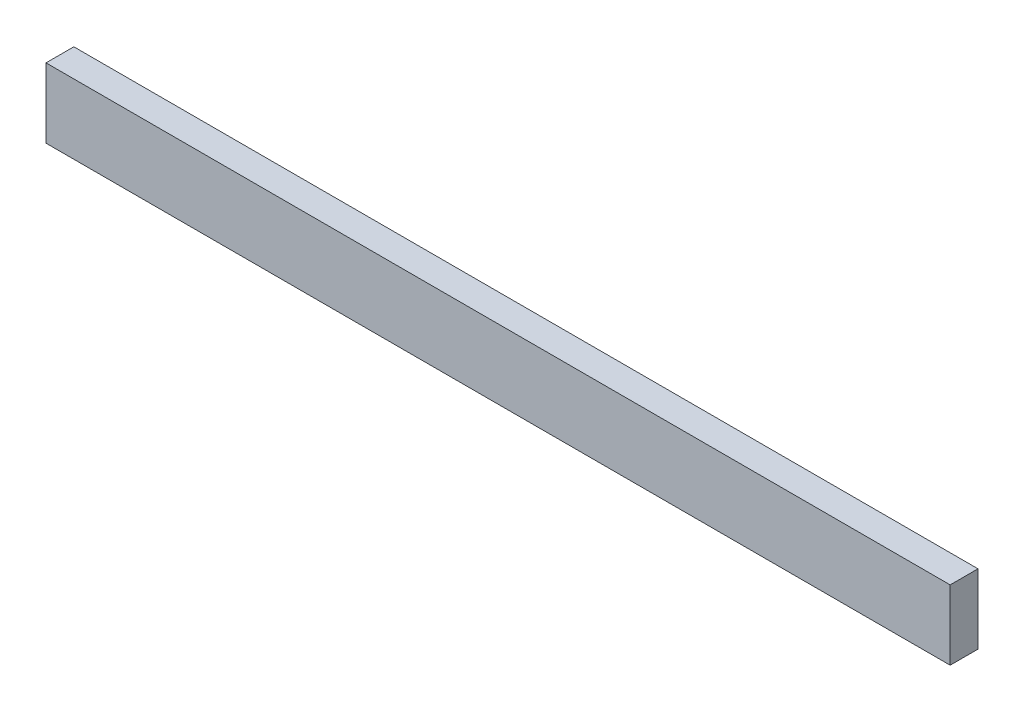
SolidWorks part; units mm, degrees
material "Cedar"
ref_plane "Front Plane" through (0, 0, 0) normal (0, 0, 1) x (1, 0, 0)
ref_plane "Top Plane" through (0, 0, 0) normal (0, 1, 0) x (1, 0, 0)
ref_plane "Right Plane" through (0, 0, 0) normal (1, 0, 0) x (0, 0, -1)
sketch "Sketch1" plane through (0, 0, 0) normal (0, 0, 1) x (1, 0, 0)
  line L1 (-162.4, 0) -> (162.4, 0)
  line L2 (-162.4, 0) -> (-162.4, 25)
  line L3 (-162.4, 25) -> (162.4, 25)
  line L4 (162.4, 0) -> (162.4, 25)
extrude "Boss-Extrude1" add sketch "Sketch1" along normal blind 10
